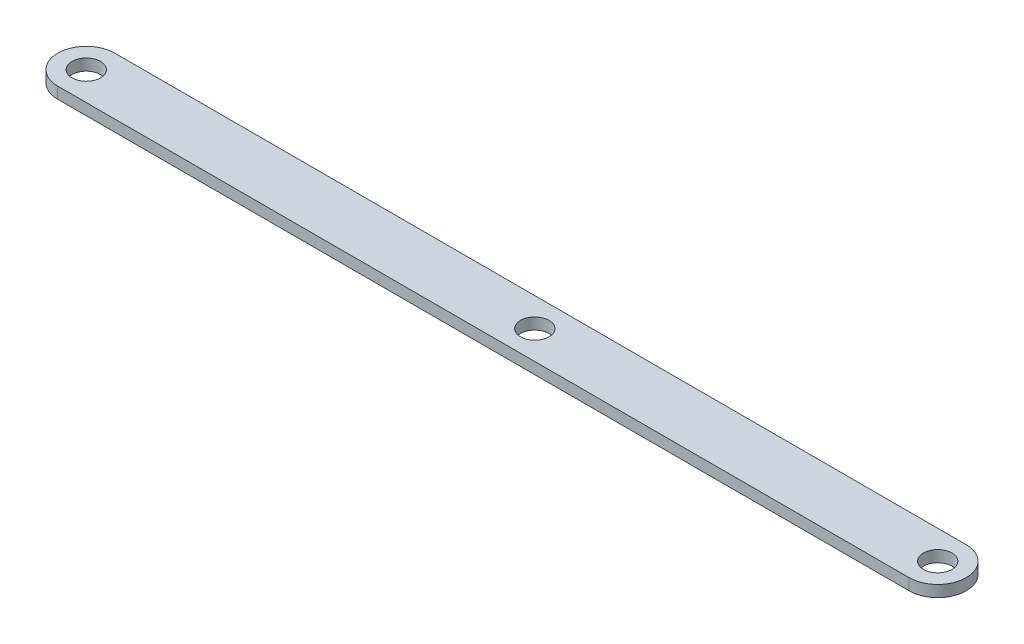
SolidWorks part; units mm, degrees
ref_plane "Front Plane" through (0, 0, 0) normal (0, 0, 1) x (1, 0, 0)
ref_plane "Top Plane" through (0, 0, 0) normal (0, 1, 0) x (1, 0, 0)
ref_plane "Right Plane" through (0, 0, 0) normal (1, 0, 0) x (0, 0, -1)
sketch "Sketch2" plane through (0, 0, 0) normal (0, 1, 0) x (1, 0, 0)
  line L0 (0, 0) -> (0, 12.7) construction
  line L1 (0, 0) -> (0, -12.7) construction
  line L2 (0, 0) -> (12.7, 0) construction
  line L3 (0, 0) -> (-179.3, 0) construction
  line L4 (-179.3, 0) -> (-378.9, 0) construction
  line L5 (-378.9, 0) -> (-391.6, 0) construction
  line L6 (-378.9, 0) -> (-378.9, 12.7) construction
  line L7 (-378.9, 0) -> (-378.9, -12.7) construction
  line L8 (-378.9, 12.7) -> (0, 12.7)
  line L9 (0, -12.7) -> (-378.9, -12.7)
  circle A0 centre (0, 0) radius 6.35
  arc A1 (0, 12.7) -> (0, -12.7) centre (0, 0) cw
  circle A2 centre (-179.3, 0) radius 6.35
  circle A3 centre (-378.9, 0) radius 6.35
  arc A4 (-378.9, 12.7) -> (-378.9, -12.7) centre (-378.9, 0) ccw
  dimension "D1" = 12.7
  dimension "D2" = 12.7
  dimension "D6" = 12.7
  dimension "D8" = 12.7
  dimension "D3" = 12.7
  dimension "D4" = 12.7
  dimension "D5" = 179.3
  dimension "D7" = 199.6
  dimension "D9" = 12.7
extrude "Boss-Extrude1" add sketch "Sketch2" along normal blind 5.08
ref_point "Point1"
